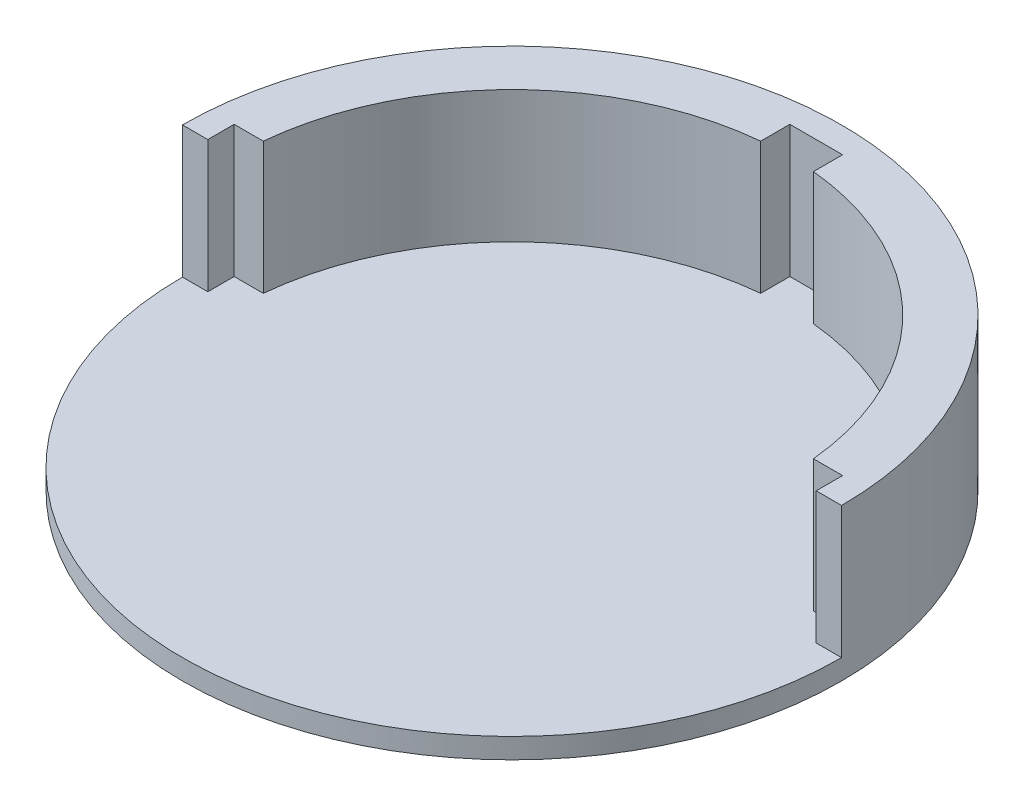
SolidWorks part; units mm, degrees
ref_plane "Front Plane" through (0, 0, 0) normal (0, 0, 1) x (1, 0, 0)
ref_plane "Top Plane" through (0, 0, 0) normal (0, 1, 0) x (1, 0, 0)
ref_plane "Right Plane" through (0, 0, 0) normal (1, 0, 0) x (0, 0, -1)
sketch "Sketch1" plane through (0, 0, 0) normal (0, 1, 0) x (1, 0, 0)
  circle A0 centre (0, 0) radius 32.5
  dimension "D1" = 65
extrude "Boss-Extrude1" add sketch "Sketch1" along normal blind 2
sketch "Sketch2" plane through (0, 2, 0) normal (0, 1, 0) x (1, 0, 0)
  line L0 (0, -55) -> (0, 55) construction
  line L1 (2.6, -30) -> (-2.6, -30)
  line L2 (2.6, -30) -> (2.6, -26.0456)
  line L3 (2.6, -26.0456) -> (-2.6, -26.0456)
  line L4 (-2.6, -30) -> (-2.6, -26.0456)
  line L5 (2.6, -30) -> (-2.6, -26.0456) construction
  line L6 (2.6, -26.0456) -> (-2.6, -30) construction
  line L7 (-30, -2.6) -> (-30, 2.6)
  line L8 (-30, -2.6) -> (-26.0456, -2.6)
  line L9 (-30, 2.6) -> (-26.0456, 2.6)
  line L10 (-26.0456, -2.6) -> (-26.0456, 2.6)
  line L11 (-2.6, 30) -> (2.6, 30)
  line L12 (-2.6, 30) -> (-2.6, 26.0456)
  line L13 (2.6, 30) -> (2.6, 26.0456)
  line L14 (-2.6, 26.0456) -> (2.6, 26.0456)
  line L15 (30, 2.6) -> (30, -2.6)
  line L16 (30, 2.6) -> (26.0456, 2.6)
  line L17 (30, -2.6) -> (26.0456, -2.6)
  line L18 (26.0456, 2.6) -> (26.0456, -2.6)
  circle A0 centre (0, 0) radius 27.1
  circle A1 centre (0, 0) radius 27.25
  circle A2 centre (0, 0) radius 32.5
  point P4 (0, -28.0228)
  circle M7 centre (0, 0) radius 32.5
  dimension "D1" = 54.5
  dimension "D2" = 54.2
  dimension "D3" = 30
  dimension "D4" = 5.2
  dimension "D5" = 4
extrude "Boss-Extrude2" add sketch "Sketch2" along normal blind 13 contours A0 L2 L1 L4 L8 L7 L9 L12 L11 L13 L16 L15 L17 M7
sketch "Sketch3" plane through (0, 0, 0) normal (0, -1, 0) x (1, 0, 0)
  circle A5 centre (0, 0) radius 5
  dimension "D1" = 10
extrude "Cut-Extrude2" [suppressed] cut sketch "Sketch3" against normal up to next contours A5
sketch "Sketch5" plane through (0, 0, 0) normal (0, -1, 0) x (1, 0, 0)
  line L1 (-9, -5.5) -> (9, -5.5) construction
  line L2 (-9, -5.5) -> (-9, 5.5) construction
  line L3 (-9, 5.5) -> (9, 5.5) construction
  line L4 (9, -5.5) -> (9, 5.5) construction
  line L5 (-9, -5.5) -> (9, 5.5) construction
  line L6 (-9, 5.5) -> (9, -5.5) construction
  circle A0 centre (9, 5.5) radius 1.3
  circle A1 centre (9, -5.5) radius 1.3
  circle A2 centre (-9, -5.5) radius 1.3
  circle A3 centre (-9, 5.5) radius 1.3
  point P0 (0, 0)
  dimension "D1" = 2.6
  dimension "D2" = 18
  dimension "D3" = 11
extrude "Cut-Extrude3" [suppressed] cut sketch "Sketch5" against normal up to next
sketch "Sketch6" plane through (0, 15, 0) normal (0, 1, 0) x (1, 0, 0)
  line L0 (-8.25, 0) -> (8.25, 0) construction
  line L1 (35.8547, 0) -> (-35.5353, 0)
  line L2 (35.8547, 0) -> (35.8547, -35.7749)
  line L3 (35.8547, -35.7749) -> (-35.5353, -35.7749)
  line L4 (-35.5353, 0) -> (-35.5353, -35.7749)
extrude "Cut-Extrude4" cut sketch "Sketch6" against normal up to surface (13 mm away) up to face at (0, 2, 0)
sketch "Sketch7" [suppressed] plane through (0, 0, 0) normal (1, 0, 0) x (0, 0, -1)
  line L0 (0, 8.25) -> (0, -8.25) construction
  line L1 (0, 2) -> (12, 2)
  line L2 (0, 2) -> (0, 5)
  line L3 (0, 5) -> (12, 5)
  line L4 (12, 2) -> (12, 5)
  line L5 (0, 2) -> (-32.5, 2) construction
  dimension "D1" = 3
  dimension "D2" = 12
